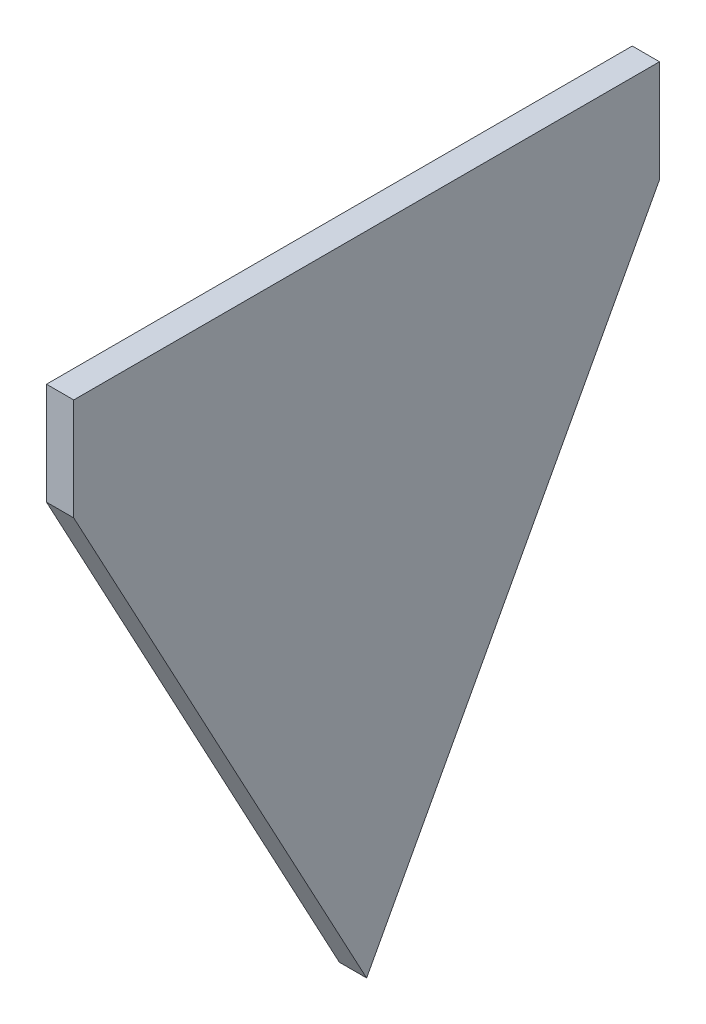
SolidWorks part; units mm, degrees
material "Acrylic (Medium-high impact)"
ref_plane "Front Plane" through (0, 0, 0) normal (0, 0, 1) x (1, 0, 0)
ref_plane "Top Plane" through (0, 0, 0) normal (0, 1, 0) x (1, 0, 0)
ref_plane "Right Plane" through (0, 0, 0) normal (1, 0, 0) x (0, 0, -1)
sketch "Sketch1" plane through (0, 0, 0) normal (1, 0, 0) x (0, 0, -1)
  line L0 (-43, 47.5) -> (43, 47.5)
  line L1 (43, 47.5) -> (43, 32.5)
  line L2 (43, 32.5) -> (0, -47.5)
  line L3 (0, -47.5) -> (-43, 32.5)
  line L4 (-43, 32.5) -> (-43, 47.5)
  line L5 (0, -47.5) -> (0, 47.5) construction
  point P2 (0, 0)
  dimension "D1" = 95
  dimension "D2" = 15
  dimension "D3" = 86
extrude "Boss-Extrude1" add sketch "Sketch1" along normal blind 4
